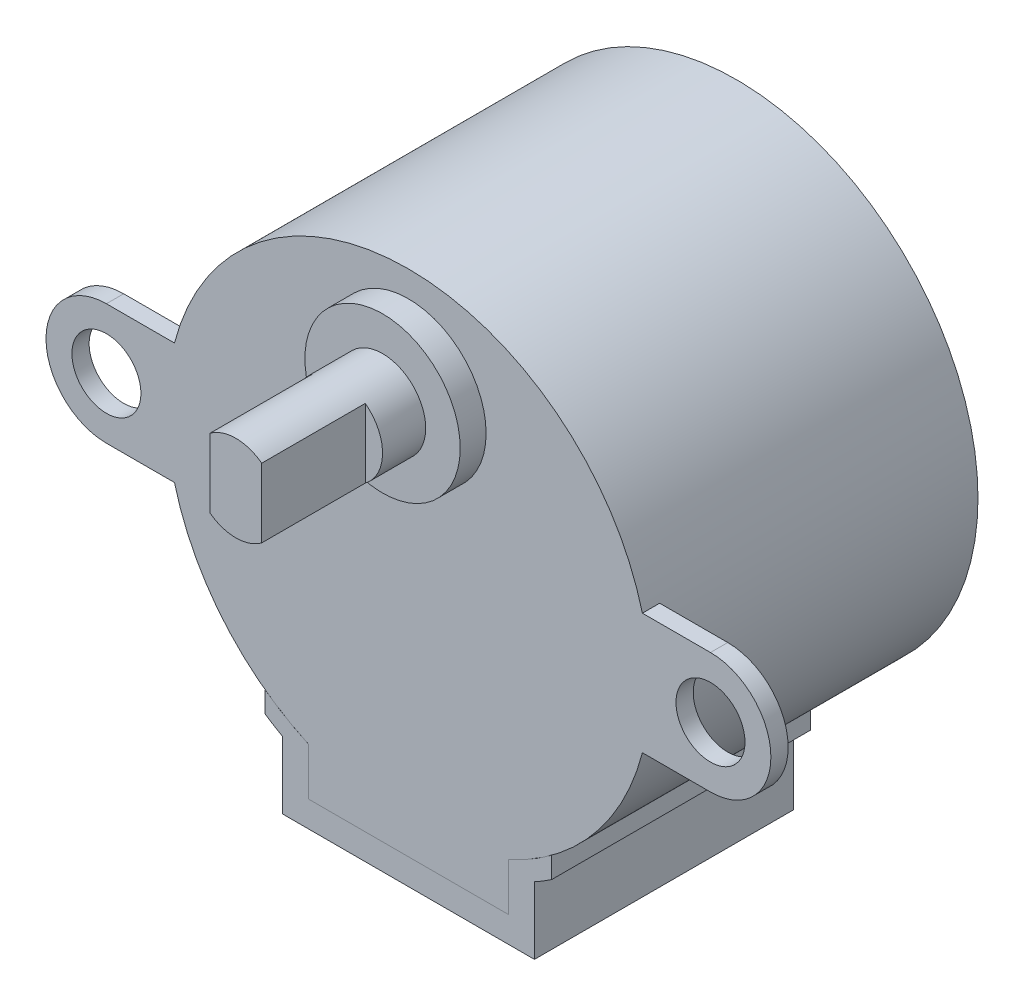
SolidWorks part; units mm, degrees
ref_plane "Front Plane" through (0, 0, 0) normal (0, 0, 1) x (1, 0, 0)
ref_plane "Top Plane" through (0, 0, 0) normal (0, 1, 0) x (1, 0, 0)
ref_plane "Right Plane" through (0, 0, 0) normal (1, 0, 0) x (0, 0, -1)
sketch "Sketch1" plane through (0, 0, 0) normal (0, 0, 1) x (1, 0, 0)
  circle A0 centre (0, 0) radius 14
  dimension "D1" = 28
extrude "Boss-Extrude1" add sketch "Sketch1" against normal blind 19 contours A0
sketch "Sketch2" plane through (0, 0, 0) normal (0, 0, 1) x (1, 0, 0)
  line L0 (-17.5, 3.5) -> (-13.5554, 3.5)
  line L1 (-17.5, -3.5) -> (-13.5554, -3.5)
  line L2 (0, 0) -> (0, -11.6148)
  line L3 (17.5, -3.5) -> (13.5554, -3.5)
  line L4 (17.5, 3.5) -> (13.5554, 3.5)
  arc A0 (-17.5, 3.5) -> (-17.5, -3.5) centre (-17.5, 0) ccw
  circle A1 centre (-17.5, 0) radius 2
  circle A2 centre (0, 0) radius 14 construction
  circle A3 centre (0, 0) radius 14
  circle A4 centre (17.5, 0) radius 2
  arc A5 (17.5, 3.5) -> (17.5, -3.5) centre (17.5, 0) cw
  circle M4 centre (0, 0) radius 14
  dimension "D1" = 7
  dimension "D3" = 4
  dimension "D2" = 17.5
extrude "Boss-Extrude2" add sketch "Sketch2" against normal blind 1 contours L0 A0 L1 A1 M4 | A5 L4 L3 A4 M4
sketch "Sketch3" plane through (0, 0, 0) normal (0, 0, 1) x (1, 0, 0)
  circle A0 centre (0, 8) radius 4.5
  dimension "D2" = 9
  dimension "D1" = 8
extrude "Boss-Extrude3" add sketch "Sketch3" along normal blind 1.5
sketch "Sketch4" plane through (0, 0, 1.5) normal (0, 0, 1) x (1, 0, 0)
  circle A0 centre (0, 8) radius 2.5
  dimension "D1" = 5
extrude "Boss-Extrude4" add sketch "Sketch4" along normal blind 8.5 separate body
sketch "Sketch5" plane through (0, 0, 10) normal (0, 0, 1) x (1, 0, 0)
  line L0 (0, 10.5) -> (0, 5.5) construction
  line L1 (-1.5, 10) -> (-1.5, 6)
  line L2 (1.5, 10) -> (1.5, 6)
  line L3 (-1.5, 11.7984) -> (-1.5, 2.788) construction
  line L4 (0, 11.7984) -> (0, 2.788) construction
  line L5 (1.5, 11.7984) -> (1.5, 2.788) construction
  circle A0 centre (0, 8) radius 2.5 construction
  circle A1 centre (0, 8) radius 2.5
  circle M3 centre (0, 8) radius 2.5
  dimension "D1" = 1.5
  dimension "D2" = 1.5
extrude "Cut-Extrude1" cut sketch "Sketch5" against normal blind 6 contours L1 M3 | L2 M3 | A1
sketch "Sketch6" plane through (0, 0, 0) normal (0, 0, 1) x (1, 0, 0)
  line L0 (-7.3, -17) -> (7.3, -17)
  line L1 (0, -14) -> (0, -17) construction
  line L2 (-7.3, -13.1038) -> (-7.3, -17)
  line L3 (7.3, -13.1038) -> (7.3, -17)
  line L4 (-7.3, 0) -> (-7.3, -18.3341) construction
  line L5 (0, 0) -> (0, -18.3341) construction
  line L6 (7.3, 0) -> (7.3, -18.3341) construction
  line L7 (-5.8, -12.7421) -> (-5.8, -15.5)
  line L8 (-5.8, -15.5) -> (5.8, -15.5)
  line L9 (5.8, -12.7421) -> (5.8, -15.5)
  line L10 (-5.8, -11.9461) -> (-5.8, -15.5) construction
  line L11 (5.8, -11.9461) -> (5.8, -15.5) construction
  line L12 (-8.3, -11.2743) -> (-8.3, -12.4944)
  line L13 (8.3, -11.2743) -> (8.3, -12.4944)
  line L14 (-8.3, -11.9461) -> (-8.3, -17) construction
  line L15 (8.3, -11.9461) -> (8.3, -17) construction
  line L16 (7.3, -11.9461) -> (7.3, -17) construction
  line L17 (-7.3, -11.9461) -> (-7.3, -17) construction
  line L18 (13.5554, -3.5) -> (17.5, -3.5)
  line L19 (17.5, 3.5) -> (13.5554, 3.5)
  line L20 (-13.5554, 3.5) -> (-17.5, 3.5)
  line L21 (-17.5, -3.5) -> (-13.5554, -3.5)
  line L22 (13.5554, -3.5) -> (17.5, -3.5)
  line L23 (17.5, 3.5) -> (13.5554, 3.5)
  line L24 (-13.5554, 3.5) -> (-17.5, 3.5)
  line L25 (-17.5, -3.5) -> (-13.5554, -3.5)
  arc A0 (-13.5554, -3.5) -> (13.5554, -3.5) centre (0, 0) ccw construction
  arc A1 (-13.5554, -3.5) -> (13.5554, -3.5) centre (0, 0) ccw
  arc A2 (-8.3, -12.4944) -> (-7.3, -13.1038) centre (0, 0) ccw
  arc A3 (-14.5237, -3.75) -> (14.5237, -3.75) centre (0, 0) ccw construction
  arc A5 (7.3, -13.1038) -> (8.3, -12.4944) centre (0, 0) ccw
  arc A7 (-13.5554, -3.5) -> (13.5554, -3.5) centre (0, 0) ccw
  arc A8 (17.5, -3.5) -> (17.5, 3.5) centre (17.5, 0) ccw
  arc A9 (13.5554, 3.5) -> (-13.5554, 3.5) centre (0, 0) ccw
  arc A10 (-17.5, 3.5) -> (-17.5, -3.5) centre (-17.5, 0) ccw
  arc A11 (-13.5554, -3.5) -> (13.5554, -3.5) centre (0, 0) ccw
  arc A12 (17.5, -3.5) -> (17.5, 3.5) centre (17.5, 0) ccw
  arc A13 (13.5554, 3.5) -> (-13.5554, 3.5) centre (0, 0) ccw
  arc A14 (-17.5, 3.5) -> (-17.5, -3.5) centre (-17.5, 0) ccw
  arc M22 (-13.5554, -3.5) -> (13.5554, -3.5) centre (0, 0) ccw
  dimension "D3" = 1.5
  dimension "D1" = 7.3
  dimension "D2" = 7.3
  dimension "D4" = 1
  dimension "D5" = 1
  dimension "D6" = 1
  dimension "D7" = 0
extrude "Boss-Extrude6" add sketch "Sketch6" against normal blind 15 separate body contours L3 A5 L13 L9 L8 L7 L12 A2 L2 L0 M22
sketch "Sketch9" plane through (0, 0, 0) normal (0, 0, 1) x (1, 0, 0)
  line L4 (13.5554, -3.5) -> (17.5, -3.5)
  line L5 (17.5, 3.5) -> (13.5554, 3.5)
  line L6 (-13.5554, 3.5) -> (-17.5, 3.5)
  line L7 (-17.5, -3.5) -> (-13.5554, -3.5)
  line L8 (13.5554, -3.5) -> (17.5, -3.5)
  line L9 (17.5, 3.5) -> (13.5554, 3.5)
  line L10 (-13.5554, 3.5) -> (-17.5, 3.5)
  line L11 (-17.5, -3.5) -> (-13.5554, -3.5)
  line L16 (7.3, -17) -> (7.3, -13.1038)
  line L17 (8.3, -12.4944) -> (8.3, -11.2743)
  line L18 (5.8, -12.7421) -> (5.8, -15.5)
  line L19 (5.8, -15.5) -> (-5.8, -15.5)
  line L20 (-5.8, -15.5) -> (-5.8, -12.7421)
  line L21 (-8.3, -11.2743) -> (-8.3, -12.4944)
  line L22 (-7.3, -13.1038) -> (-7.3, -17)
  line L23 (-7.3, -17) -> (7.3, -17)
  line L26 (5.8, -12.7421) -> (5.8, -15.5)
  line L27 (5.8, -15.5) -> (-5.8, -15.5)
  line L28 (-5.8, -15.5) -> (-5.8, -12.7421)
  arc A4 (-13.5554, -3.5) -> (13.5554, -3.5) centre (0, 0) ccw
  arc A5 (17.5, -3.5) -> (17.5, 3.5) centre (17.5, 0) ccw
  arc A6 (13.5554, 3.5) -> (-13.5554, 3.5) centre (0, 0) ccw
  arc A7 (-17.5, 3.5) -> (-17.5, -3.5) centre (-17.5, 0) ccw
  arc A8 (-5.8, -12.7421) -> (5.8, -12.7421) centre (0, 0) ccw
  arc A9 (17.5, -3.5) -> (17.5, 3.5) centre (17.5, 0) ccw
  arc A10 (13.5554, 3.5) -> (-13.5554, 3.5) centre (0, 0) ccw
  arc A11 (-17.5, 3.5) -> (-17.5, -3.5) centre (-17.5, 0) ccw
  arc A12 (7.3, -13.1038) -> (8.3, -12.4944) centre (0, 0) ccw
  arc A13 (5.8, -12.7421) -> (8.3, -11.2743) centre (0, 0) ccw
  arc A14 (-8.3, -11.2743) -> (-5.8, -12.7421) centre (0, 0) ccw
  arc A15 (-8.3, -12.4944) -> (-7.3, -13.1038) centre (0, 0) ccw
  dimension "D1" = 0
  dimension "D2" = 0
extrude "Boss-Extrude7" add sketch "Sketch9" against normal blind 15 contours L28 L27 L26 L5
sketch "Sketch10" plane through (0, -17, 0) normal (0, -1, 0) x (-1, 0, 0)
  line L0 (0, 0) -> (0, 15) construction
  line L1 (3.25, 1) -> (-3.25, 1)
  line L2 (3.25, 1) -> (3.25, 2.5)
  line L3 (3.25, 2.5) -> (-3.25, 2.5)
  line L4 (-3.25, 1) -> (-3.25, 2.5)
  line L5 (3.25, 1) -> (-3.25, 2.5) construction
  line L6 (3.25, 2.5) -> (-3.25, 1) construction
  line L7 (5.8, 15) -> (-5.8, 15) construction
  line L8 (7.3, 0) -> (-7.3, 0) construction
  point P0 (0, 1.75)
  dimension "D1" = 1.5
  dimension "D2" = 6.5
  dimension "D3" = 2.5
extrude "Cut-Extrude2" cut sketch "Sketch10" against normal up to vertex (1.5 mm away)
